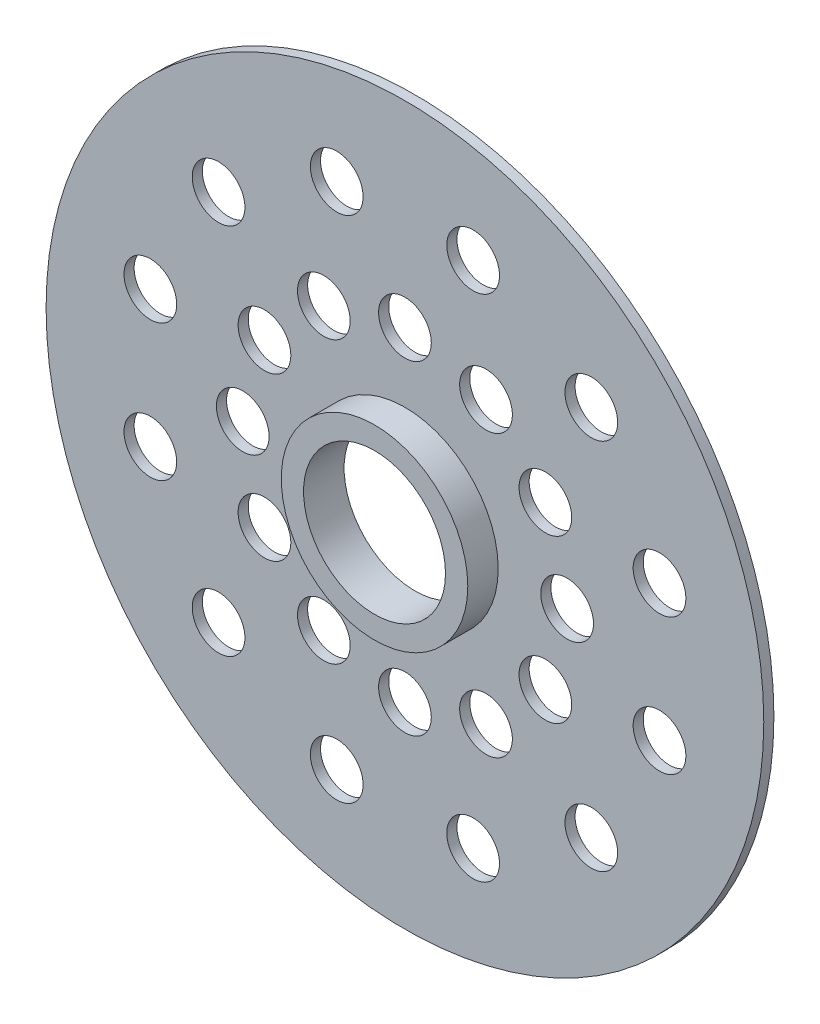
SolidWorks part; units mm, degrees
ref_plane "Спереди" through (0, 0, 0) normal (0, 0, 1) x (1, 0, 0)
ref_plane "Сверху" through (0, 0, 0) normal (0, 1, 0) x (1, 0, 0)
ref_plane "Справа" through (0, 0, 0) normal (1, 0, 0) x (0, 0, -1)
sketch "Эскиз1" plane through (0, 0, 0) normal (0, 0, 1) x (1, 0, 0)
  circle A0 centre (0, 0) radius 88.5
  circle A1 centre (0, 0) radius 17.5
extrude "Rear_cover_reference" add sketch "Эскиз1" along normal blind 2.5 from offset 42
sketch "Эскиз2" plane through (0, 0, 0) normal (0, 0, 1) x (1, 0, 0)
  circle A0 centre (0, 0) radius 23
  circle A1 centre (0, 0) radius 17.5
extrude "Bearing_boss_reference" add sketch "Эскиз2" along normal blind 10 from offset 42
sketch "Эскиз3" plane through (0, 0, 0) normal (0, 0, 1) x (1, 0, 0)
  circle A0 centre (40, 0) radius 6.5
  circle A1 centre (34.641, 20) radius 6.5
  circle A2 centre (20, 34.641) radius 6.5
  circle A3 centre (0, 40) radius 6.5
  circle A4 centre (-20, 34.641) radius 6.5
  circle A5 centre (-34.641, 20) radius 6.5
  circle A6 centre (-40, 0) radius 6.5
  circle A7 centre (-34.641, -20) radius 6.5
  circle A8 centre (-20, -34.641) radius 6.5
  circle A9 centre (0, -40) radius 6.5
  circle A10 centre (20, -34.641) radius 6.5
  circle A11 centre (34.641, -20) radius 6.5
  circle A12 centre (62.7852, 16.8232) radius 6.5
  circle A13 centre (45.9619, 45.9619) radius 6.5
  circle A14 centre (16.8232, 62.7852) radius 6.5
  circle A15 centre (-16.8232, 62.7852) radius 6.5
  circle A16 centre (-45.9619, 45.9619) radius 6.5
  circle A17 centre (-62.7852, 16.8232) radius 6.5
  circle A18 centre (-62.7852, -16.8232) radius 6.5
  circle A19 centre (-45.9619, -45.9619) radius 6.5
  circle A20 centre (-16.8232, -62.7852) radius 6.5
  circle A21 centre (16.8232, -62.7852) radius 6.5
  circle A22 centre (45.9619, -45.9619) radius 6.5
  circle A23 centre (62.7852, -16.8232) radius 6.5
extrude "Through_holes" cut sketch "Эскиз3" against normal mid plane 200
